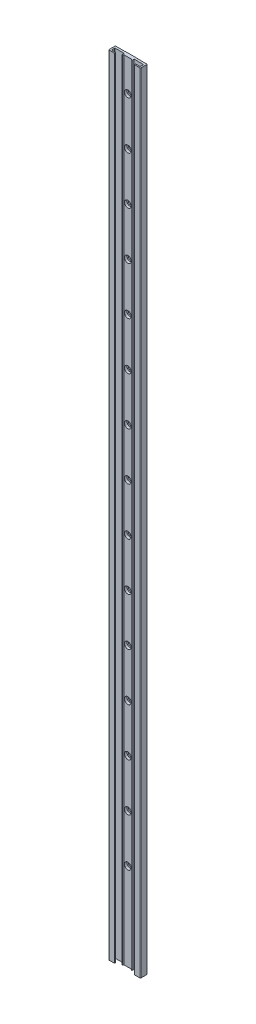
SolidWorks part; units mm, degrees
ref_plane "Plan de face" through (0, 0, 0) normal (0, 0, 1) x (1, 0, 0)
ref_plane "Plan de dessus" through (0, 0, 0) normal (0, 1, 0) x (1, 0, 0)
ref_plane "Plan de droite" through (0, 0, 0) normal (1, 0, 0) x (0, 0, -1)
ref_plane "Plan1" through (0, 0, 8.7) normal (0, 0, 1) x (1, 0, 0)
sketch "Esquisse1" plane through (0, 0, 8.7) normal (0, 0, 1) x (1, 0, 0)
  line L0 (20, 200) -> (-20, 200)
  line L1 (-20, 200) -> (-20, -790)
  line L2 (-20, -790) -> (20, -790)
  line L3 (20, -790) -> (20, 200)
  dimension "D1" = 40
  dimension "D2" = 990
extrude "Boss.-Extru.1" add sketch "Esquisse1" against normal blind 8.7
sketch "Esquisse2" plane through (0, 200, 0) normal (0, 1, 0) x (-1, 0, 0)
  line L0 (12.5, 8.7) -> (-12.5, 8.7)
  line L1 (-12.5, 8.7) -> (-12.5, 7.2)
  line L2 (-12.5, 7.2) -> (-18, 7.2)
  line L3 (-18, 7.2) -> (-18, 2.8)
  line L4 (-18, 2.8) -> (-6.3, 2.8)
  line L5 (-6.3, 2.8) -> (-6.3, 5.5)
  line L6 (-6.3, 5.5) -> (-5.75, 5.5)
  line L7 (-5.75, 5.5) -> (-4.75, 4.5)
  line L8 (-4.75, 4.5) -> (4.75, 4.5)
  line L9 (4.75, 4.5) -> (5.75, 5.5)
  line L10 (5.75, 5.5) -> (6.3, 5.5)
  line L11 (6.3, 5.5) -> (6.3, 2.8)
  line L12 (6.3, 2.8) -> (18, 2.8)
  line L13 (18, 2.8) -> (18, 7.2)
  line L14 (18, 7.2) -> (12.5, 7.2)
  line L15 (12.5, 7.2) -> (12.5, 8.7)
extrude "Enlèv. mat.-Extru.1" cut sketch "Esquisse2" against normal through all
sketch "Esquisse3" plane through (0, 200, 0) normal (0, 1, 0) x (-1, 0, 0)
  line L0 (20, 0.2) -> (8, 0.2)
  line L1 (8, 0.2) -> (8, 0)
  line L2 (8, 0) -> (20, 0)
  line L3 (20, 0) -> (20, 0.2)
extrude "Enlèv. mat.-Extru.2" cut sketch "Esquisse3" against normal through all
sketch "Esquisse4" plane through (0, 200, 0) normal (0, 1, 0) x (-1, 0, 0)
  line L0 (-8, 0.2) -> (-20, 0.2)
  line L1 (-20, 0.2) -> (-20, 0)
  line L2 (-20, 0) -> (-8, 0)
  line L3 (-8, 0) -> (-8, 0.2)
extrude "Enlèv. mat.-Extru.3" cut sketch "Esquisse4" against normal through all
hole_wizard "Chambrage pour vis à tête hexagonale M41" positions "Esquisse6" profile "Esquisse5" counterbore size "M4" standard "Ansi Metric"
sketch "Esquisse6" plane through (0, 0, 4.5) normal (0, 0, 1) x (1, 0, 0)
  point P0 (0, 40)
  point P1 (0, 100)
  point P2 (0, 160)
sketch "Esquisse5" plane through (0, 40, 4.5) normal (1, 0, 0) x (0, -1, 0)
  line L0 (0, 0) -> (0, 4.5)
  line L1 (0, 4.5) -> (2.25, 4.5)
  line L3 (2.25, 4.5) -> (2.25, 3.1)
  line L4 (2.25, 3.1) -> (4.25, 3.1)
  line L5 (4.25, 3.1) -> (4.25, 0)
  line L7 (4.25, 0) -> (0, 0)
  line L11 (0, -6.35) -> (0, 107.95) construction
  dimension "Diamètre du perçage jusqu'au prochain" = 4.5
  dimension "Profondeur du perçage jusqu'au prochain" = 4.5
  dimension "Diamètre du chambrage" = 8.5
  dimension "Profondeur du chambrage" = 3.1
fillet "Congé1" radius 0.5 6 edges at (18, -295, 7.2) (18, -295, 2.8) (20, -295, 0.2) (-18, -295, 7.2) (-20, -295, 0.2) (-18, -295, 2.8)
fillet "Congé2" radius 1 2 edges at (-20, -295, 8.7) (20, -295, 8.7)
pattern_linear "Répétition linéaire1" count 13 spacing 60 along (0, -1, 0) of "Chambrage pour vis à tête hexagonale M41"
